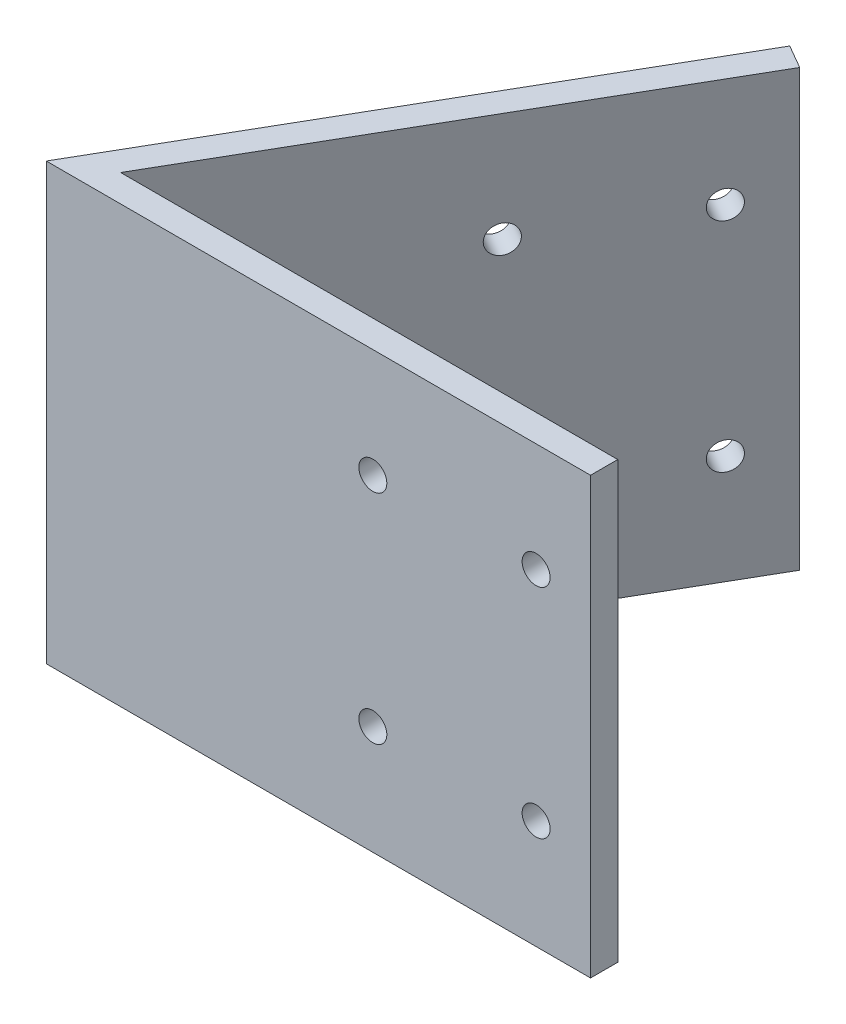
SolidWorks part; units mm, degrees
material "6061 Alloy"
ref_plane "Front Plane" through (0, 0, 0) normal (0, 0, 1) x (1, 0, 0)
ref_plane "Top Plane" through (0, 0, 0) normal (0, 1, 0) x (1, 0, 0)
ref_plane "Right Plane" through (0, 0, 0) normal (1, 0, 0) x (0, 0, -1)
sketch "Sketch1" plane through (0, 0, 0) normal (0, 1, 0) x (1, 0, 0)
  line L0 (0, 0) -> (31.75, 54.9926)
  line L1 (31.75, 54.9926) -> (34.4996, 53.4051)
  line L2 (34.4996, 53.4051) -> (5.4993, 3.175)
  line L3 (5.4993, 3.175) -> (63.5, 3.175)
  line L4 (63.5, 3.175) -> (63.5, 0)
  line L5 (63.5, 0) -> (0, 0)
  dimension "D1" = 60
  dimension "D2" = 3.175
  dimension "D3" = 63.5
  dimension "D4" = 63.5
  dimension "D5" = 3.175
extrude "Boss-Extrude1" add sketch "Sketch1" along normal blind 50.8
hole_wizard "#30 (0.1285) Diameter Hole1" positions "Sketch3" profile "Sketch2" hole size "#30" standard "ANSI Inch" end condition up to next
sketch "Sketch3" plane through (0, 0, 0) normal (0, 0, 1) x (1, 0, 0)
  line L0 (0, 0) -> (63.5, 0) construction
  line L1 (0, 50.8) -> (63.5, 50.8) construction
  line L2 (63.5, 50.8) -> (63.5, 0) construction
  line L3 (0, 50.8) -> (0, 0) construction
  point P0 (57.15, 12.7)
  point P2 (57.15, 38.1)
  point P4 (38.1, 38.1)
  point P6 (38.1, 12.7)
  dimension "D1" = 12.7
  dimension "D2" = 12.7
  dimension "D3" = 6.35
  dimension "D4" = 6.35
  dimension "D5" = 12.7
  dimension "D6" = 12.7
  dimension "D7" = 38.1
  dimension "D8" = 38.1
sketch "Sketch2" plane through (57.15, 12.7, 0) normal (1, 0, 0) x (0, -1, 0)
  line L0 (0, 0) -> (0, 3.175)
  line L1 (0, 3.175) -> (1.6319, 3.175)
  line L2 (1.6319, 3.175) -> (1.6319, 0)
  line L5 (1.6319, 0) -> (0, 0)
  line L11 (0, -6.35) -> (0, 107.95) construction
  dimension "Thru Hole Dia." = 3.2639
  dimension "Thru Hole Depth" = 3.175
hole_wizard "#30 (0.1285) Diameter Hole2" positions "Sketch5" profile "Sketch4" hole size "#30" standard "ANSI Inch"
sketch "Sketch5" plane through (0, 0, 0) normal (-0.866, 0, -0.5) x (-0.5, 0, 0.866)
  line L0 (-63.5, 50.8) -> (0, 50.8) construction
  line L1 (-63.5, 50.8) -> (-63.5, 0) construction
  line L2 (-63.5, 0) -> (0, 0) construction
  line L3 (0, 50.8) -> (0, 0) construction
  point P0 (-57.15, 38.1)
  point P2 (-57.15, 12.7)
  point P4 (-38.1, 12.7)
  point P6 (-38.1, 38.1)
  dimension "D1" = 12.7
  dimension "D2" = 6.35
  dimension "D3" = 12.7
  dimension "D4" = 6.35
  dimension "D5" = 38.1
  dimension "D6" = 38.1
  dimension "D7" = 12.7
  dimension "D8" = 12.7
sketch "Sketch4" plane through (28.575, 38.1, -49.4934) normal (0, 1, 0) x (-0.5, 0, 0.866)
  line L0 (0, 0) -> (0, 26.3806)
  line L1 (0, 26.3806) -> (1.6319, 25.4)
  line L2 (1.6319, 25.4) -> (1.6319, 0)
  line L5 (1.6319, 0) -> (0, 0)
  line L10 (0, 26.3806) -> (-1.6319, 25.4) construction
  line L11 (0, -6.35) -> (0, 107.95) construction
  dimension "Hole Dia." = 3.2639
  dimension "Hole Depth" = 25.4
  dimension "Drill Angle" = 118
